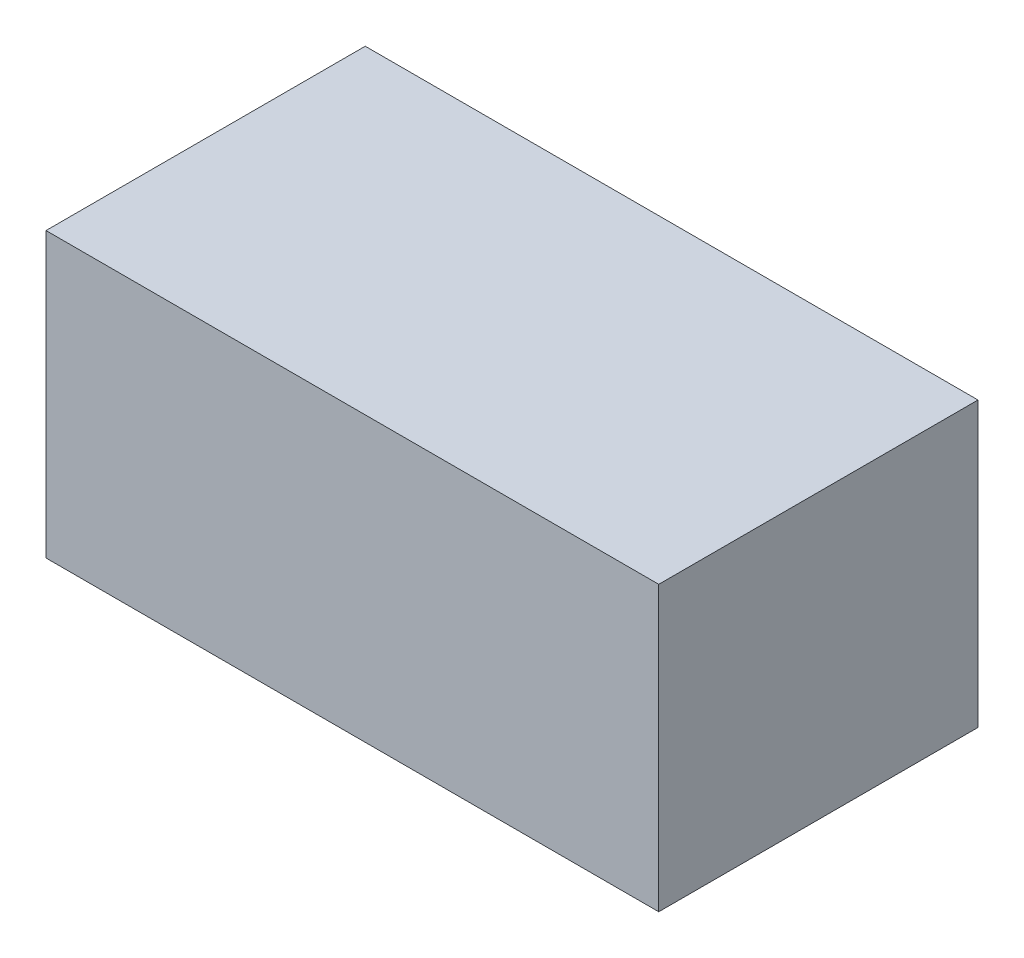
SolidWorks part; units mm, degrees
ref_plane "Front Plane" through (0, 0, 0) normal (0, 0, 1) x (1, 0, 0)
ref_plane "Top Plane" through (0, 0, 0) normal (0, 1, 0) x (1, 0, 0)
ref_plane "Right Plane" through (0, 0, 0) normal (1, 0, 0) x (0, 0, -1)
sketch "Sketch1" plane through (0, 0, 0) normal (0, 1, 0) x (1, 0, 0)
  line L0 (0, 0) -> (59.817, 0) construction
  line L1 (0, 15.5829) -> (59.817, 15.5829)
  line L2 (0, 15.5829) -> (0, -15.5829)
  line L3 (0, -15.5829) -> (59.817, -15.5829)
  line L4 (59.817, 15.5829) -> (59.817, -15.5829)
  dimension "D1" = 59.817
  dimension "D2" = 31.1658
extrude "Boss-Extrude1" add sketch "Sketch1" along normal blind 27.686
